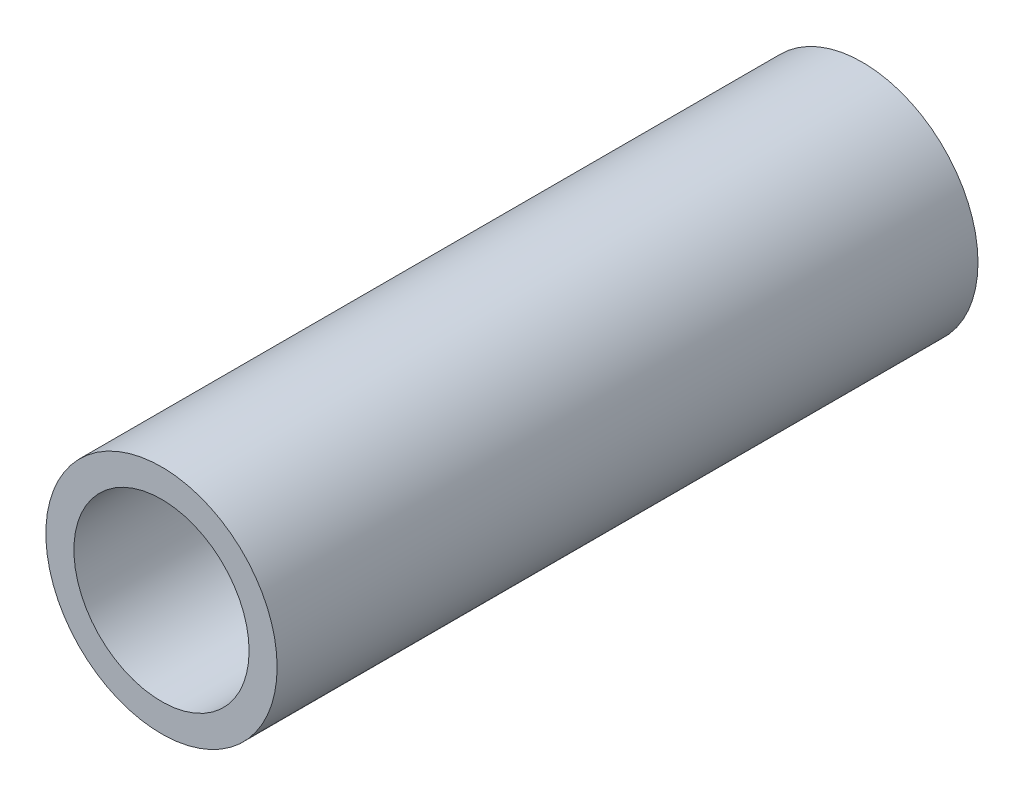
SolidWorks part; units mm, degrees
ref_plane "前视基准面" through (0, 0, 0) normal (0, 0, 1) x (1, 0, 0)
ref_plane "上视基准面" through (0, 0, 0) normal (0, 1, 0) x (1, 0, 0)
ref_plane "右视基准面" through (0, 0, 0) normal (1, 0, 0) x (0, 0, -1)
sketch "草图1" plane through (0, 0, 0) normal (0, 0, 1) x (1, 0, 0)
  circle A0 centre (0, 0) radius 16.5
  circle A1 centre (0, 0) radius 12.5
  dimension "D1" = 25
  dimension "D2" = 33
extrude "凸台-拉伸1" add sketch "草图1" along normal blind 100
